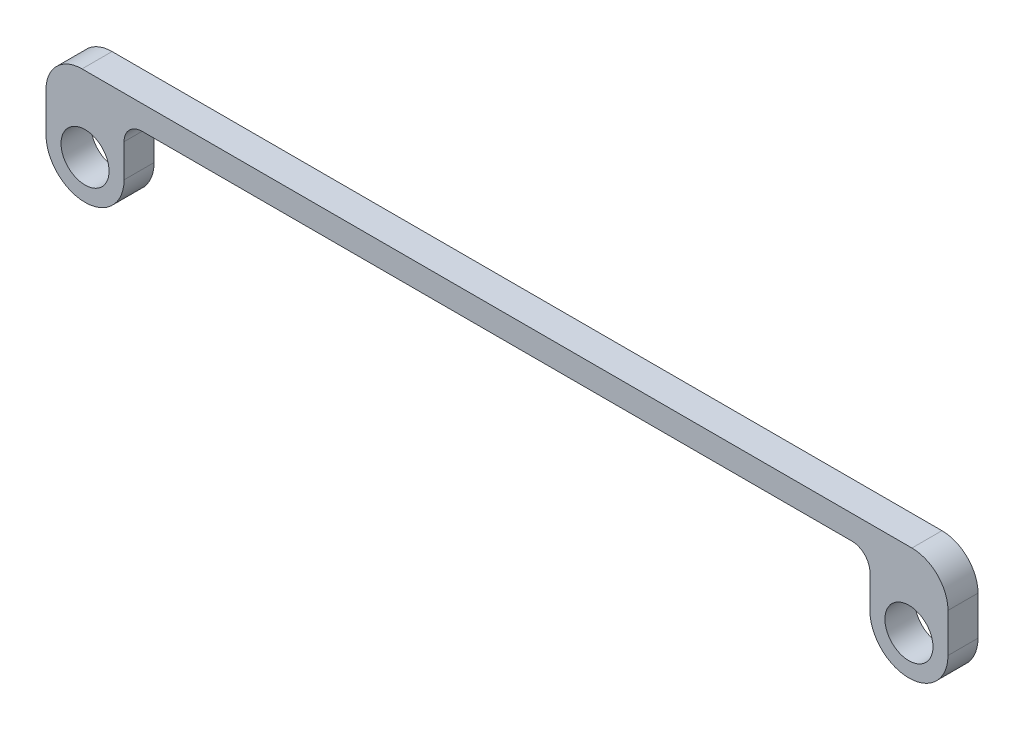
SolidWorks part; units mm, degrees
ref_plane "Front Plane" through (0, 0, 0) normal (0, 0, 1) x (1, 0, 0)
ref_plane "Top Plane" through (0, 0, 0) normal (0, 1, 0) x (1, 0, 0)
ref_plane "Right Plane" through (0, 0, 0) normal (1, 0, 0) x (0, 0, -1)
sketch "Sketch1" plane through (0, 0, 0) normal (0, 0, 1) x (1, 0, 0)
  line L1 (0, 0) -> (130.17, 0)
  line L2 (0, 0) -> (0, -4)
  line L3 (13, -4) -> (137.17, -4)
  line L8 (0, -4) -> (0, -12.5)
  line L10 (13, -4) -> (13, -12.5)
  line L19 (130.17, 0) -> (150.17, 0)
  line L22 (150.17, 0) -> (150.17, -4)
  line L26 (150.17, -4) -> (150.17, -12.5)
  line L28 (137.17, -4) -> (137.17, -12.5)
  arc A0 (0, -12.5) -> (13, -12.5) centre (6.5, -12.5) ccw
  arc A2 (137.17, -12.5) -> (150.17, -12.5) centre (143.67, -12.5) ccw
  point P5 (65.085, -2)
  point P11 (14.7784, -18.7491)
  point P26 (143.67, -8.25)
  dimension "D5" = 4
  dimension "D1" = 137.17
  dimension "D2" = 4
  dimension "D3" = 130.17
extrude "Boss-Extrude1" add sketch "Sketch1" along normal blind 5
sketch "Sketch2" plane through (0, 0, 5) normal (0, 0, 1) x (1, 0, 0)
  circle A0 centre (6.5, -12.5) radius 4
  circle A1 centre (143.67, -12.5) radius 4
extrude "Cut-Extrude1" cut sketch "Sketch2" against normal through all
fillet "Fillet1" radius 6 2 edges at (0, 0, 2.5) (150.17, 0, 2.5)
fillet "Fillet2" radius 3 2 edges at (13, -4, 2.5) (137.17, -4, 2.5)
